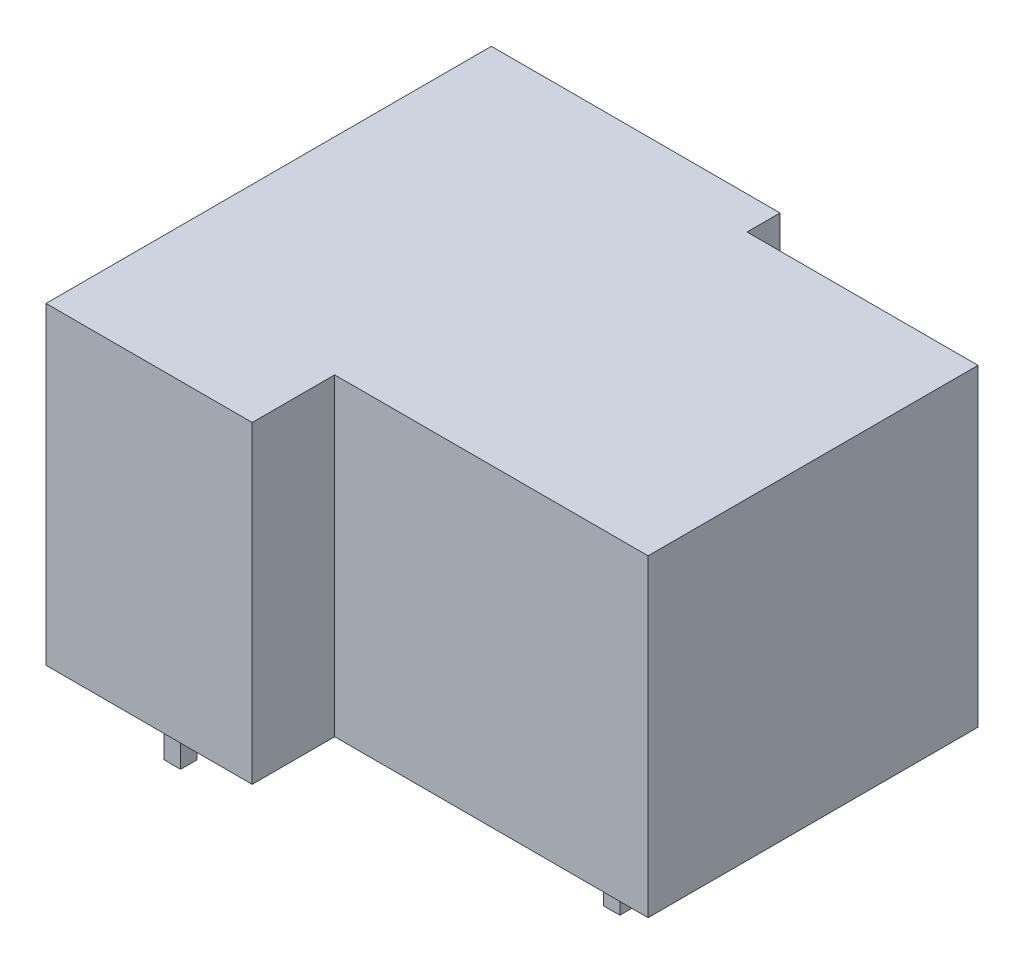
SolidWorks part; units mm, degrees
ref_plane "前视基准面" through (0, 0, 0) normal (0, 0, 1) x (1, 0, 0)
ref_plane "上视基准面" through (0, 0, 0) normal (0, 1, 0) x (1, 0, 0)
ref_plane "右视基准面" through (0, 0, 0) normal (1, 0, 0) x (0, 0, -1)
sketch "草图1" plane through (0, 0, 0) normal (0, 1, 0) x (1, 0, 0)
  line L0 (0, 41.7773) -> (0, -45.7415) construction
  line L1 (5, 10) -> (19, 10)
  line L2 (0, -10) -> (0, -15)
  line L3 (0, -10) -> (19, -10)
  line L4 (19, 10) -> (19, -10)
  line L5 (-48.486, 0) -> (58.5492, 0) construction
  line L6 (0, -15) -> (-12.5, -15)
  line L7 (-12.5, -15) -> (-12.5, 12)
  line L8 (-12.5, 12) -> (5, 12)
  line L9 (5, 12) -> (5, 10)
  point P12 (-6.25, -15)
  point P14 (0, -12.5)
  dimension "D1" = 27
  dimension "D2" = 20
  dimension "D3" = 5
  dimension "D4" = 31.5
  dimension "D5" = 19
  dimension "D6" = 14
extrude "拉伸1" add sketch "草图1" along normal blind 19
sketch "草图2" plane through (0, 0, 0) normal (0, -1, 0) x (1, 0, 0)
  line L1 (14.3316, -8.5224) -> (13.3316, -8.5224)
  line L2 (14.3316, -8.5224) -> (14.3316, -7.5224)
  line L3 (14.3316, -7.5224) -> (13.3316, -7.5224)
  line L4 (13.3316, -8.5224) -> (13.3316, -7.5224)
  line L5 (13.8316, -9.6475) -> (13.8316, -6.8936) construction
  line L8 (14.5169, 7.2264) -> (13.5169, 7.2264)
  line L9 (14.5169, 7.2264) -> (14.5169, 6.2264)
  line L10 (14.5169, 6.2264) -> (13.5169, 6.2264)
  line L11 (13.5169, 7.2264) -> (13.5169, 6.2264)
  line L13 (14.0169, 4.8939) -> (14.0169, 7.944) construction
  line L14 (-6.46, 12.8823) -> (-7.46, 12.8823)
  line L15 (-6.46, 12.8823) -> (-6.46, 11.8823)
  line L16 (-6.46, 11.8823) -> (-7.46, 11.8823)
  line L17 (-7.46, 12.8823) -> (-7.46, 11.8823)
  line L18 (-6.96, 7.128) -> (-6.96, 5.1977) construction
  line L20 (-1.7892, -9.7777) -> (-1.7892, -8.7777)
  line L21 (-0.7892, -8.7777) -> (-1.7892, -8.7777)
  line L22 (-0.7892, -9.7777) -> (-0.7892, -8.7777)
  line L23 (-0.7892, -9.7777) -> (-1.7892, -9.7777)
  line L24 (-10.4594, -9.8386) -> (-10.4594, -8.8386)
  line L25 (-9.4594, -8.8386) -> (-10.4594, -8.8386)
  line L26 (-9.4594, -9.8386) -> (-9.4594, -8.8386)
  line L27 (-9.4594, -9.8386) -> (-10.4594, -9.8386)
  dimension "D1" = 1
  dimension "D2" = 1
  dimension "D4" = 1
  dimension "D5" = 1
  dimension "D8" = 1
  dimension "D9" = 1
extrude "拉伸2" add sketch "草图2" along normal blind 3.5
